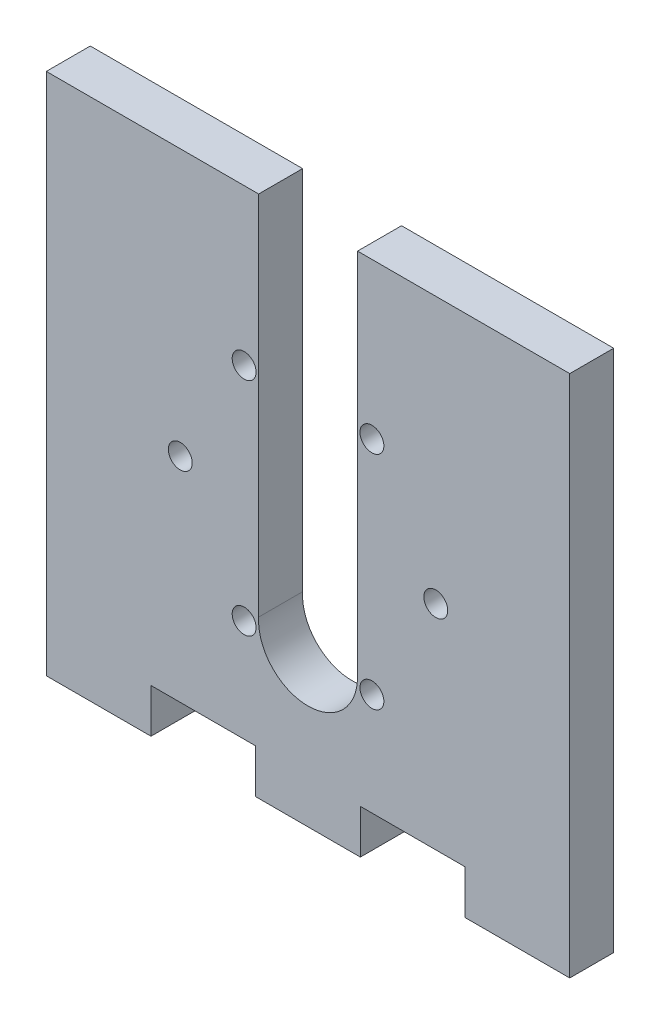
SolidWorks part; units mm, degrees
material "Oak"
ref_plane "Front Plane" through (0, 0, 0) normal (0, 0, 1) x (1, 0, 0)
ref_plane "Top Plane" through (0, 0, 0) normal (0, 1, 0) x (1, 0, 0)
ref_plane "Right Plane" through (0, 0, 0) normal (1, 0, 0) x (0, 0, -1)
sketch "Sketch2" plane through (0, 0, 0) normal (0, 0, 1) x (1, 0, 0)
  line L1 (0, 0) -> (63.5, 0)
  line L2 (0, 0) -> (0, 63.5)
  line L3 (0, 63.5) -> (63.5, 63.5)
  line L4 (63.5, 0) -> (63.5, 63.5)
  dimension "D1" = 63.5
  dimension "D2" = 63.5
extrude "Boss-Extrude1" add sketch "Sketch2" along normal blind 5.334
sketch "Sketch4" plane through (0, 0, 5.334) normal (0, 0, 1) x (1, 0, 0)
  line L0 (0, 0) -> (63.5, 0) construction
  line L1 (12.7, 0) -> (25.4, 0)
  line L2 (12.7, 0) -> (12.7, 5.334)
  line L3 (12.7, 5.334) -> (25.4, 5.334)
  line L4 (25.4, 0) -> (25.4, 5.334)
  line L5 (63.5, 0) -> (63.5, 63.5) construction
  line L6 (38.1, 0) -> (50.8, 0)
  line L7 (38.1, 0) -> (38.1, 5.334)
  line L8 (38.1, 5.334) -> (50.8, 5.334)
  line L9 (50.8, 0) -> (50.8, 5.334)
  line L10 (0, 63.5) -> (0, 0) construction
  dimension "D1" = 5.334
  dimension "D2" = 5.334
  dimension "D3" = 12.7
  dimension "D4" = 12.7
  dimension "D5" = 12.7
  dimension "D6" = 12.7
extrude "Cut-Extrude1" cut sketch "Sketch4" against normal blind 5.334
sketch "Sketch5" plane through (0, 0, 5.334) normal (0, 0, 1) x (1, 0, 0)
  line L0 (63.5, 0) -> (63.5, 63.5) construction
  line L1 (63.5, 63.5) -> (0, 63.5) construction
  circle A0 centre (31.75, 18.7) radius 6
  dimension "D1" = 12
  dimension "D2" = 31.75
  dimension "D3" = 44.8
extrude "Cut-Extrude2" cut sketch "Sketch5" against normal blind 5.334
sketch "Sketch6" plane through (0, 0, 5.334) normal (0, 0, 1) x (1, 0, 0)
  line L0 (63.5, 63.5) -> (0, 63.5) construction
  line L1 (25.7602, 19.0494) -> (37.7602, 19.0494)
  line L2 (25.7602, 19.0494) -> (25.7602, 63.5)
  line L3 (25.7602, 63.5) -> (37.7602, 63.5)
  line L4 (37.7602, 19.0494) -> (37.7602, 63.5)
  circle A0 centre (31.75, 18.7) radius 6 construction
  dimension "D1" = 12
extrude "Cut-Extrude3" cut sketch "Sketch6" against normal blind 5.334
sketch "Sketch7" plane through (0, 0, 5.334) normal (0, 0, 1) x (1, 0, 0)
  line L0 (31.75, 31.2) -> (34.7219, 31.2) construction
  circle A0 centre (47.25, 31.2) radius 1.45
  circle A1 centre (47.25, 31.2) radius 1.45 construction
  circle A2 centre (39.5, 17.7766) radius 1.45
  circle A3 centre (24, 17.7766) radius 1.45
  circle A4 centre (16.25, 31.2) radius 1.45
  circle A5 centre (24, 44.6234) radius 1.45
  circle A6 centre (39.5, 44.6234) radius 1.45
  point P21 (31.75, 31.2)
  dimension "D1" = 6
extrude "Cut-Extrude4" cut sketch "Sketch7" against normal through all
equation "\"Base_Width\"= 10in"
equation "\"Base_Length\"= 10in"
equation "\"Wheel_Width\"= 3in"
equation "\"MDF\"= 0.21in"
equation "\"D1@Boss-Extrude1\"=\"MDF\""
equation "\"D1@Sketch4\"=\"MDF\""
equation "\"D2@Sketch4\"=\"MDF\""
equation "\"D1@Cut-Extrude1\"=\"MDF\""
equation "\"D1@Cut-Extrude2\"=\"MDF\""
equation "\"D1@Cut-Extrude3\"=\"MDF\""
equation "\"D1@Sketch5\"=12mm"
equation "\"D3@Sketch5\"=2in-(12mm/2)"
